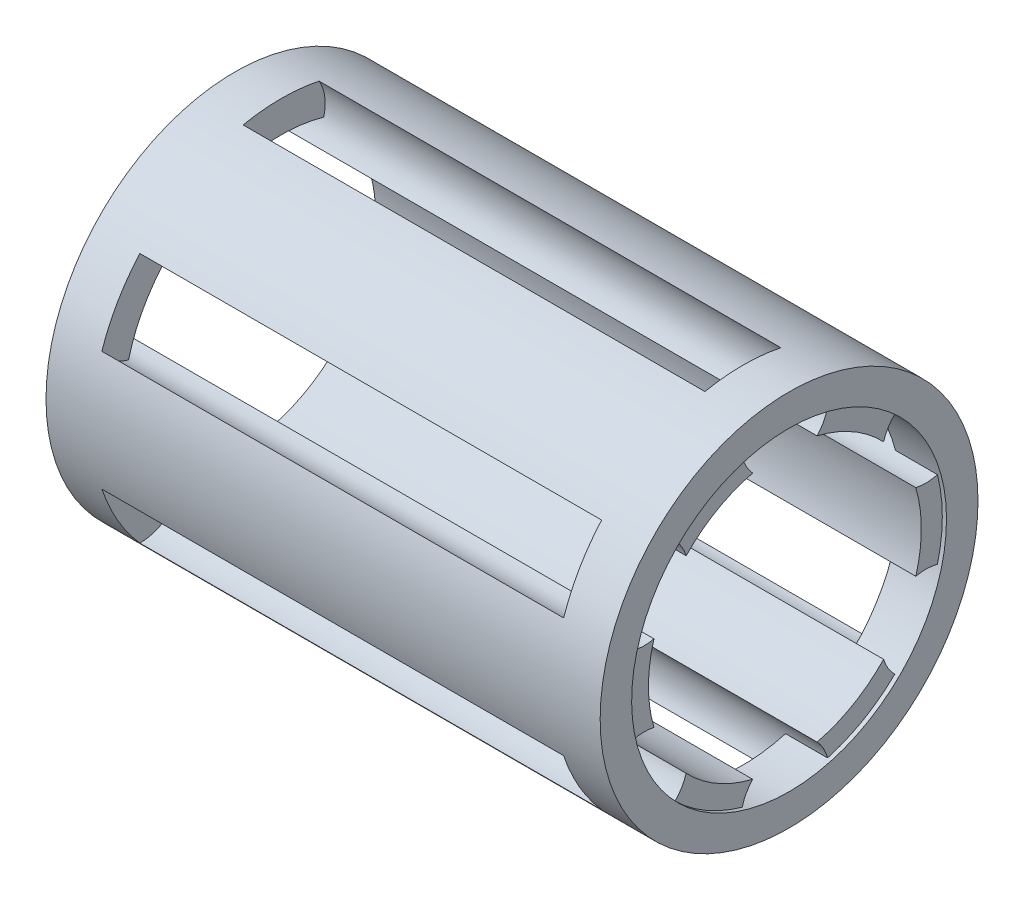
SolidWorks part; units mm, degrees
material "CA"
ref_plane "Front Plane" through (0, 0, 0) normal (0, 0, 1) x (1, 0, 0)
ref_plane "Top Plane" through (0, 0, 0) normal (0, 1, 0) x (1, 0, 0)
ref_plane "Right Plane" through (0, 0, 0) normal (1, 0, 0) x (0, 0, -1)
sketch "Sketch1" plane through (0, 0, 0) normal (1, 0, 0) x (0, 0, -1)
  arc A1 (-1.8092, 8.8163) -> (-6.7306, 5.9749) centre (0, 0) ccw
  arc A3 (-1.5344, 6.3163) -> (-4.7029, 4.487) centre (0, 0) ccw
  arc A5 (-1.8092, 8.8163) -> (-1.5344, 6.3163) centre (0, 7.75) ccw
  arc A6 (6.2373, 1.8293) -> (8.5397, 2.8414) centre (6.7117, 3.875) ccw
  arc A7 (8.5397, -2.8414) -> (6.2373, -1.8293) centre (6.7117, -3.875) ccw
  arc A8 (-1.5344, -6.3163) -> (-1.8092, -8.8163) centre (0, -7.75) ccw
  arc A9 (-6.7306, -5.9749) -> (-4.7029, -4.487) centre (-6.7117, -3.875) ccw
  arc A10 (-4.7029, 4.487) -> (-6.7306, 5.9749) centre (-6.7117, 3.875) ccw
  circle A11 centre (0, 0) radius 9 construction
  circle A12 centre (0, 0) radius 6.5 construction
  arc A13 (1.5344, 6.3163) -> (1.8092, 8.8163) centre (0, 7.75) ccw
  arc A14 (-6.2373, 1.8293) -> (-6.2373, -1.8293) centre (0, 0) ccw
  arc A15 (-8.5397, 2.8414) -> (-8.5397, -2.8414) centre (0, 0) ccw
  arc A16 (-8.5397, 2.8414) -> (-6.2373, 1.8293) centre (-6.7117, 3.875) ccw
  arc A17 (-6.7306, -5.9749) -> (-1.8092, -8.8163) centre (0, 0) ccw
  arc A18 (-4.7029, -4.487) -> (-1.5344, -6.3163) centre (0, 0) ccw
  arc A19 (-6.2373, -1.8293) -> (-8.5397, -2.8414) centre (-6.7117, -3.875) ccw
  arc A20 (4.7029, 4.487) -> (1.5344, 6.3163) centre (0, 0) ccw
  arc A21 (6.7306, 5.9749) -> (1.8092, 8.8163) centre (0, 0) ccw
  arc A22 (6.7306, 5.9749) -> (4.7029, 4.487) centre (6.7117, 3.875) ccw
  arc A23 (8.5397, -2.8414) -> (8.5397, 2.8414) centre (0, 0) ccw
  arc A24 (6.2373, -1.8293) -> (6.2373, 1.8293) centre (0, 0) ccw
  arc A25 (4.7029, -4.487) -> (6.7306, -5.9749) centre (6.7117, -3.875) ccw
  arc A26 (1.5344, -6.3163) -> (4.7029, -4.487) centre (0, 0) ccw
  arc A27 (1.8092, -8.8163) -> (6.7306, -5.9749) centre (0, 0) ccw
  arc A28 (1.8092, -8.8163) -> (1.5344, -6.3163) centre (0, -7.75) ccw
  point P22 (0, 0)
  dimension "D1" = 18
  dimension "D4" = 4.2
  dimension "D2" = 2.5
  dimension "D5" = 6
extrude "Boss-Extrude1" add sketch "Sketch1" along normal blind 26
sketch "Sketch2" plane through (26, 0, 0) normal (1, 0, 0) x (0, 0, -1)
  circle A0 centre (0, 0) radius 9
  circle A1 centre (0, 0) radius 7.5
  dimension "D1" = 1.5
extrude "Boss-Extrude2" add sketch "Sketch2" against normal blind 2 and the other way blind 0.2
sketch "Sketch3" plane through (0, 0, 0) normal (-1, 0, 0) x (0, 0, 1)
  circle A0 centre (0, 0) radius 9
  circle A1 centre (0, 0) radius 7.5
  dimension "D1" = 1.5
extrude "Boss-Extrude3" add sketch "Sketch3" against normal blind 2 and the other way blind 0.2
